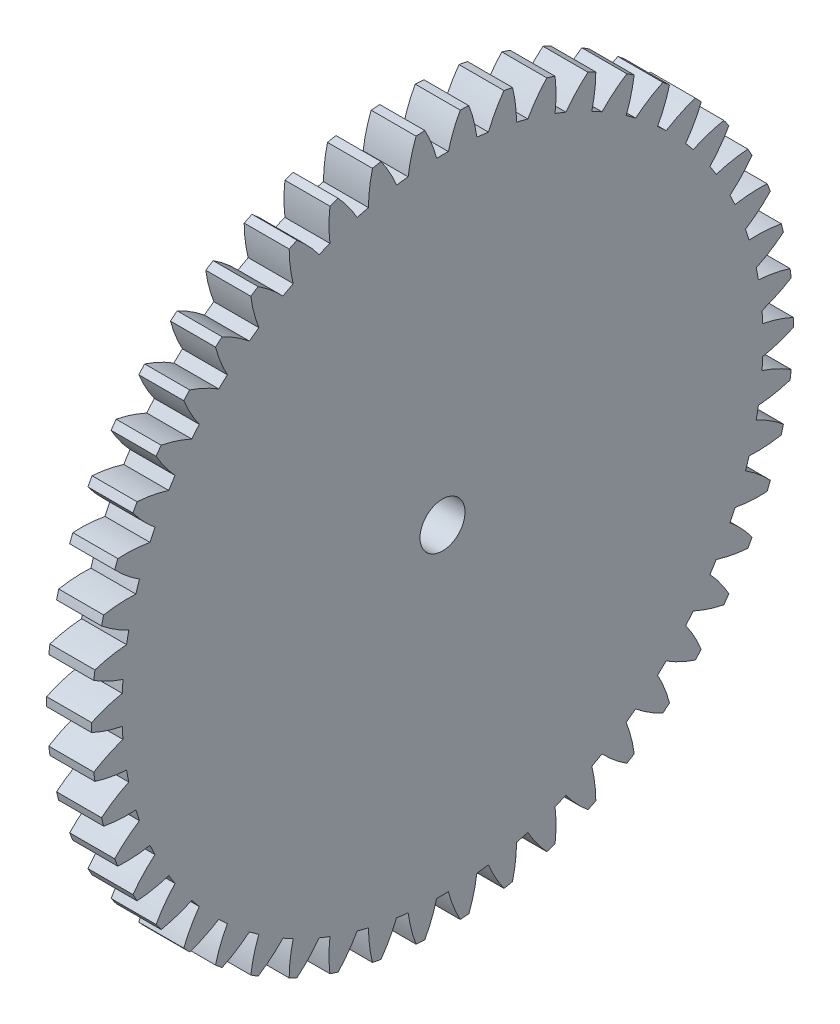
SolidWorks part; units mm, degrees
ref_plane "Plane1" through (0, 0, 0) normal (0, 0, 1) x (1, 0, 0)
ref_plane "Plane2" through (0, 0, 0) normal (0, 1, 0) x (1, 0, 0)
ref_plane "Plane3" through (0, 0, 0) normal (1, 0, 0) x (0, 0, -1)
sketch "HoldingSke" plane through (0, 0, 0) normal (0, 1, 0) x (1, 0, 0)
  line L0 (0, 0) -> (0.4285, -0.5107)
  line L1 (-15, 0) -> (100, 0) construction
  line L2 (0, 0) -> (-2.1039, 2.3779)
  line L3 (0, 0) -> (-11.863, 4.5341)
  line L4 (0, 0) -> (5.5511, 6.6156)
  line L5 (0, 0) -> (-9.3695, -3.4946)
  line L6 (0, 0) -> (-4.1448, -2.7965)
  line L7 (-2.1039, 2.3779) -> (0.0486, 12.1435)
  line L8 (-76.2, 54.61) -> (-75.3, 54.61)
  line L9 (-71.009, 38.7566) -> (-53.1078, 45.2721)
  line L10 (-76.2, 71.12) -> (104.1128, 71.12)
  line L11 (0, 0) -> (-5, 0)
  line L12 (-76.2, 101.6) -> (-76.147, 101.6)
  line L13 (24.9733, 27.94) -> (52.9518, 28.4284)
  line L14 (24.9733, 27.94) -> (24.9743, 27.94)
  line L15 (24.9733, 27.94) -> (100.4006, 29.5858)
  line L16 (-63.627, -1.5) -> (-12.827, -1.5)
  circle A0 centre (0, 0) radius 2.5
  circle A1 centre (0, 0) radius 5
  circle A2 centre (0, 0) radius 5
  circle A3 centre (0, 0) radius 2.5
  dimension "MHD" = 10
  dimension "Hub_dia" = 10
  dimension "Bore" = 5
  dimension "MBD" = 5
  dimension "Num_teeth" = 50
  dimension "Pitch" = 0.6667
  dimension "Overall_len" = 10
  dimension "Show_teeth" = 50
  dimension "Thickness" = 5
  dimension "OAL" = 10.0001
  dimension "T_dim" = 0.9
  dimension "Ap" = 20
  dimension "H" = 19.05
  dimension "Pitch_radius" = 180.3128
  dimension "Width" = 5
  dimension "Backlash" = 0.053
  dimension "Addendum_fac" = 1
  dimension "Dedendum_fac" = 1.25
  dimension "Clearance_fac" = 0.25
  dimension "Dedendum_add" = 0.001
  dimension "Module" = 1.5
sketch "BasProSke" plane through (0, 0, 0) normal (0, 1, 0) x (1, 0, 0)
  line L0 (-10, 0) -> (60, 0) construction
  line L1 (0, 0) -> (0, 39)
  line L2 (0, 0) -> (5, 0)
  line L3 (5, 0) -> (5, 39)
  line L4 (5, 39) -> (0, 39)
  dimension "Thickness" = 5
  dimension "Diameter" = 78
revolve "Base-Revolve" add sketch "BasProSke" angle 360 about L0
sketch "TooCutSke" plane through (0, 0, 0) normal (1, 0, 0) x (0, 0, -1)
  line L1 (0, 0) -> (0, 107) construction
  line L2 (0, 0) -> (-1.2706, 37.4785) construction
  line L3 (0, 0) -> (-4.7073, 74.8207) construction
  line L4 (-1.2706, 37.4785) -> (-2.3537, 37.4103) construction
  arc A0 (0.65, 35.6181) -> (-0.65, 35.6181) centre (0, 0) ccw
  arc A1 (1.9801, 38.9751) -> (-1.9801, 38.9751) centre (0, 0) ccw
  circle A2 centre (0, 0) radius 37.5 construction
  circle A3 centre (0, 0) radius 35.2385 construction
  arc A4 (-0.65, 35.6181) -> (-1.9801, 38.9751) centre (-15.1589, 31.8113) ccw
  arc A5 (1.9801, 38.9751) -> (0.65, 35.6181) centre (15.1589, 31.8113) ccw
  dimension "Root_dia" = 71.248
  dimension "Overcut_dia" = 78.0508
  dimension "Pitch_dia" = 75
  dimension "Base_dia" = 70.4769
  dimension "Flank_rad" = 15
  dimension "Half_ang" = 3.6
  dimension "Half_CT" = 1.0852
extrude "ToothCut" cut sketch "TooCutSke" along normal through all
fillet "Breaks" [suppressed] radius 0.03
fillet "RootFillets" [suppressed] radius 0.376
pattern_circular "TeethCuts" count 50 every 7.2 about axis through (-10, 0, 0) along (1, 0, 0) of "ToothCut", "RootFillets", "Breaks"
sketch "HubNeaOneSke" plane through (0, 0, 0) normal (-1, 0, 0) x (0, 0, 1)
  circle A0 centre (0, 0) radius 5
  dimension "Diameter" = 10
extrude "HubNearOne" add sketch "HubNeaOneSke" along normal blind 5.0001
sketch "HubNeaBotSke" plane through (0, 0, 0) normal (-1, 0, 0) x (0, 0, 1)
  circle A0 centre (0, 0) radius 5
  dimension "Diameter" = 10
extrude "HubNearBoth" [suppressed] add sketch "HubNeaBotSke" along normal blind 2.5
ref_plane "FarPln" through (5, 0, 0) normal (1, 0, 0) x (0, 0, -1)
sketch "HubFarSke" plane through (5, 0, 0) normal (1, 0, 0) x (0, 0, -1)
  circle A0 centre (0, 0) radius 5
  dimension "Diameter" = 10
extrude "HubFar" [suppressed] add sketch "HubFarSke" along normal blind 2.5
sketch "BorSke" plane through (0, 0, 0) normal (1, 0, 0) x (0, 0, -1)
  circle A0 centre (0, 0) radius 2.5
  dimension "Diameter" = 5
extrude "Bore" cut sketch "BorSke" along normal mid plane 20.0001
sketch "KeySke" plane through (0, 0, 0) normal (1, 0, 0) x (0, 0, -1)
  line L0 (-1, 0) -> (-1, 3.4)
  line L1 (-1, 3.4) -> (1, 3.4)
  line L2 (1, 3.4) -> (1, 0)
  line L3 (0, 0) -> (0, 34) construction
  line L4 (-1, 0) -> (1, 0)
  dimension "Offset" = 3.4
  dimension "Width" = 2
extrude "Keyway" [suppressed] cut sketch "KeySke" along normal mid plane 20.0001
pattern_circular "Keyway2" [suppressed] count 2 every 90 about axis through (-10, 0, 0) along (1, 0, 0)
equation "' \"Module@HoldingSke\" = 6.35"
equation "' \"Num_teeth@HoldingSke\" = 12"
equation "' \"Ap@HoldingSke\" =  20"
equation "' \"Ap@HoldingSke\" = 20"
equation "' \"Width@HoldingSke\" = 0.5 * 25.4"
equation "' \"Hub_dia@HoldingSke\"= 1 * 25.4"
equation "' \"Hub_dia@HoldingSke\" = 1 * 25.4"
equation "' \"Overall_len@HoldingSke\" = 1.0 * 25.4"
equation "' \"Bore@HoldingSke\" = 0.75 * 25.4"
equation "' \"T_dim@HoldingSke\" = 0.1 * 25.4"
equation "' \"Width@KeySke\" = 0.25 * 25.4"
equation "' \"Show_teeth@HoldingSke\" = 13"
equation "' \"Backlash@HoldingSke\" = 0.009 * 25.4"
equation "' \"Addendum_fac@HoldingSke\" = 1.0"
equation "' \"Dedendum_fac@HoldingSke\" = 1.25"
equation "' \"Dedendum_add@HoldingSke\" = 0.00005 * 25.4"
equation "' \"Clearance_fac@HoldingSke\" = 0.25"
equation "\"Pitch@HoldingSke\" = 1 / \"Module@HoldingSke\""
equation "\"Overcut_dia@TooCutSke\" = (\"Num_teeth@HoldingSke\" + 2 * \"Addendum_fac@HoldingSke\") / \"Pitch@HoldingSke\" + 0.002 * 25.4"
equation "\"Pitch_dia@TooCutSke\" = \"Num_teeth@HoldingSke\" / \"Pitch@HoldingSke\""
equation "\"Base_dia@TooCutSke\" = \"Num_teeth@HoldingSke\" / \"Pitch@HoldingSke\" * cos((\"Ap@HoldingSke\"  * 3.14159265 / 180))"
equation "\"Root_dia@TooCutSke\" = (\"Num_teeth@HoldingSke\" + 2) / \"Pitch@HoldingSke\" - 2 * (\"Addendum_fac@HoldingSke\" + \"Dedendum_fac@HoldingSke\") / \"Pitch@HoldingSke\" - \"Dedendum_add@HoldingSke\" * 2"
equation "\"Half_ang@TooCutSke\" = 180 / \"Num_teeth@HoldingSke\""
equation "\"Half_CT@TooCutSke\" = \"Num_teeth@HoldingSke\" / \"Pitch@HoldingSke\" * sin((3.14159265 / 2 / \"Num_teeth@HoldingSke\")) / 2 - 7 * \"Backlash@HoldingSke\" / 4"
equation "\"Flank_rad@TooCutSke\" = \"Num_teeth@HoldingSke\" / \"Pitch@HoldingSke\" / 5"
equation "\"Radius@RootFillets\" = \"Clearance_fac@HoldingSke\" / \"Pitch@HoldingSke\" + \"Dedendum_add@HoldingSke\""
equation "\"Break_rad@Breaks\" = 0.02 / \"Pitch@HoldingSke\""
equation "\"Thickness@HoldingSke\" = \"Width@HoldingSke\""
equation "\"OAL@HoldingSke\" = \"Thickness@HoldingSke\""
equation "\"MHD@HoldingSke\" = (\"Num_teeth@HoldingSke\" + 2) / \"Pitch@HoldingSke\" - 2 * (\"Addendum_fac@HoldingSke\" + \"Dedendum_fac@HoldingSke\")  / \"Pitch@HoldingSke\" - \"Dedendum_add@HoldingSke\" * 2"
equation "\"MBD@HoldingSke\" = (\"Num_teeth@HoldingSke\" + 2) / \"Pitch@HoldingSke\" - 2 * (\"Addendum_fac@HoldingSke\" + \"Dedendum_fac@HoldingSke\")  / \"Pitch@HoldingSke\" - \"Dedendum_add@HoldingSke\" * 2 - 0.002 * 25.4"
equation "\"MHD@HoldingSke\" = ((sgn( \"MHD@HoldingSke\" - \"Hub_dia@HoldingSke\" )-1)*( \"MHD@HoldingSke\" - \"Hub_dia@HoldingSke\" ))/-2+ \"Hub_dia@HoldingSke\""
equation "\"MBD@HoldingSke\" = ((sgn( \"MBD@HoldingSke\" - \"Bore@HoldingSke\" )-1)*( \"MBD@HoldingSke\" - \"Bore@HoldingSke\" ))/-2+ \"Bore@HoldingSke\""
equation "\"OAL@HoldingSke\" = ((sgn( \"OAL@HoldingSke\" - \"Overall_len@HoldingSke\" )+1)*( \"OAL@HoldingSke\" - \"Overall_len@HoldingSke\" ))/2 + \"Overall_len@HoldingSke\" + 0.000002 * 25.4"
equation "\"Num_teeth@TeethCuts\" = int( \"Show_teeth@HoldingSke\" ) + 1"
equation "\"Num_teeth@TeethCuts\" = ((sgn( \"Num_teeth@TeethCuts\" - \"Num_teeth@HoldingSke\" )-1)*( \"Num_teeth@TeethCuts\" - \"Num_teeth@HoldingSke\" ))/-2+ \"Num_teeth@HoldingSke\""
equation "\"Num_teeth@TeethCuts\" = ((sgn( \"Num_teeth@TeethCuts\" - 2.0)+1)*( \"Num_teeth@TeethCuts\" - 2.0))/2 +2.0"
equation "\"Angle@TeethCuts\" = 360.0 / \"Num_teeth@HoldingSke\""
equation "\"Diameter@BasProSke\" = (\"Num_teeth@HoldingSke\" + 2 * \"Addendum_fac@HoldingSke\") / \"Pitch@HoldingSke\""
equation "\"Thickness@BasProSke\"  = \"Thickness@HoldingSke\""
equation "' \"Fillet_rad@BasProSke\" =  \"Thickness@HoldingSke\" * 0.05"
equation "' \"Fillet_rad@BasProSke\" = \"Thickness@HoldingSke\" * 0.05"
equation "\"MHD@HoldingSke\" = ((sgn( \"MHD@HoldingSke\" - \"Root_dia@TooCutSke\" )-1)*( \"MHD@HoldingSke\" - \"Root_dia@TooCutSke\" ))/-2+ \"Root_dia@TooCutSke\""
equation "\"Diameter@HubNeaOneSke\" = \"MHD@HoldingSke\""
equation "\"Length@HubNearOne\" = \"OAL@HoldingSke\" - \"Thickness@BasProSke\""
equation "\"Diameter@HubNeaBotSke\" = \"MHD@HoldingSke\""
equation "\"Length@HubNearBoth\" = ( \"OAL@HoldingSke\" - \"Thickness@BasProSke\" ) / 2.0"
equation "\"Thickness@FarPln\" = \"Thickness@BasProSke\""
equation "\"Diameter@HubFarSke\" = \"MHD@HoldingSke\""
equation "\"Length@HubFar\" = ( \"OAL@HoldingSke\" - \"Thickness@BasProSke\" ) / 2.0"
equation "\"Diameter@BorSke\" = \"MBD@HoldingSke\""
equation "\"D1@Bore\" = \"OAL@HoldingSke\" * 2.0"
equation "\"D1@Keyway\" = \"OAL@HoldingSke\" * 2.0"
equation "\"Offset@KeySke\" = \"T_dim@HoldingSke\" + \"MBD@HoldingSke\" / 2.0"
